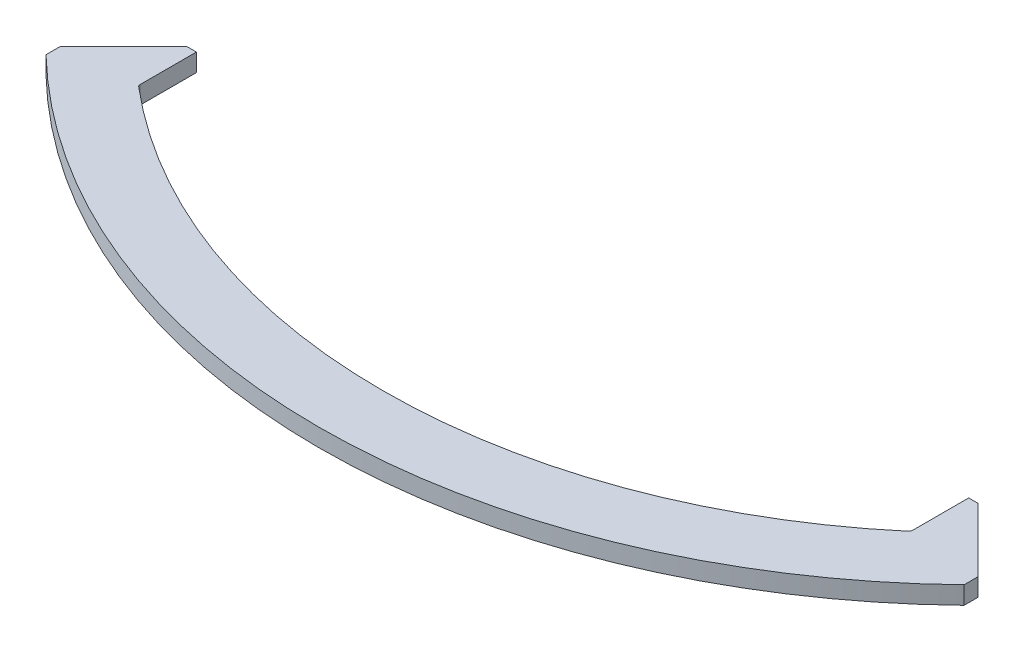
SolidWorks part; units mm, degrees
material "Pine"
ref_plane "Front Plane" through (0, 0, 0) normal (0, 0, 1) x (1, 0, 0)
ref_plane "Top Plane" through (0, 0, 0) normal (0, 1, 0) x (1, 0, 0)
ref_plane "Right Plane" through (0, 0, 0) normal (1, 0, 0) x (0, 0, -1)
sketch "Sketch1" plane through (0, 0, 0) normal (0, 1, 0) x (1, 0, 0)
  line L0 (844.55, 590.55) -> (844.55, -590.55)
  line L1 (-590.55, 862.0125) -> (590.55, 862.0125)
  line L2 (-590.55, 862.0125) -> (-590.55, -862.0125)
  line L3 (-590.55, -862.0125) -> (590.55, -862.0125)
  line L4 (590.55, 862.0125) -> (590.55, -862.0125)
  line L5 (-590.55, 862.0125) -> (590.55, -862.0125) construction
  line L6 (-590.55, -862.0125) -> (590.55, 862.0125) construction
  line L7 (-862.0125, -590.55) -> (862.0125, -590.55)
  line L8 (-862.0125, -590.55) -> (-862.0125, 590.55)
  line L9 (-862.0125, 590.55) -> (862.0125, 590.55)
  line L10 (862.0125, -590.55) -> (862.0125, 590.55)
  line L11 (-862.0125, -590.55) -> (862.0125, 590.55) construction
  line L12 (-862.0125, 590.55) -> (862.0125, -590.55) construction
  circle A0 centre (0, 0) radius 674.6875
  circle A1 centre (0, 0) radius 609.6
  dimension "D1" = 1349.375
  dimension "D2" = 65.0875
  dimension "D3" = 1181.1
  dimension "D4" = 862.0125
  dimension "D5" = 17.4625
sketch "Sketch2" plane through (0, 0, 0) normal (0, 1, 0) x (1, 0, 0)
  line L0 (439.7375, -395.2875) -> (439.7375, -484.1875) construction
  line L13 (484.1875, -484.1875) -> (395.2875, -484.1875)
  line L14 (484.1875, -484.1875) -> (484.1875, -395.2875)
  line L15 (484.1875, -395.2875) -> (395.2875, -395.2875)
  line L16 (395.2875, -484.1875) -> (395.2875, -395.2875)
  line L18 (395.2875, -439.7375) -> (484.1875, -439.7375) construction
  line L20 (-395.2875, -484.1875) -> (-395.2875, -395.2875)
  line L21 (-484.1875, -395.2875) -> (-395.2875, -395.2875)
  line L22 (-484.1875, -484.1875) -> (-484.1875, -395.2875)
  line L23 (-484.1875, -484.1875) -> (-395.2875, -484.1875)
  line L24 (-395.2875, -439.7375) -> (-484.1875, -439.7375) construction
  line L25 (-439.7375, -395.2875) -> (-439.7375, -484.1875) construction
  line L26 (-484.1875, 395.2875) -> (-395.2875, 395.2875)
  line L27 (-395.2875, 484.1875) -> (-395.2875, 395.2875)
  line L28 (-484.1875, 484.1875) -> (-395.2875, 484.1875)
  line L29 (-484.1875, 484.1875) -> (-484.1875, 395.2875)
  line L30 (-439.7375, 395.2875) -> (-439.7375, 484.1875) construction
  line L31 (-395.2875, 439.7375) -> (-484.1875, 439.7375) construction
  line L32 (395.2875, 484.1875) -> (395.2875, 395.2875)
  line L33 (484.1875, 395.2875) -> (395.2875, 395.2875)
  line L34 (484.1875, 484.1875) -> (484.1875, 395.2875)
  line L35 (484.1875, 484.1875) -> (395.2875, 484.1875)
  line L36 (395.2875, 439.7375) -> (484.1875, 439.7375) construction
  line L37 (439.7375, 395.2875) -> (439.7375, 484.1875) construction
  circle A0 centre (0, 0) radius 649.2875
  circle A2 centre (0, 0) radius 649.2875
  circle A3 centre (0, 0) radius 649.2875
  circle A4 centre (0, 0) radius 649.2875
  circle A5 centre (0, 0) radius 674.6875 construction
  point P24 (439.7375, -439.7375)
  point P48 (0, 0)
  dimension "D2" = 25.4
  dimension "D1" = 88.9
  dimension "D4" = 968.375
  dimension "D5" = 968.375
  dimension "D3" = 4
sketch "Sketch3" plane through (0, 0, 0) normal (0, 1, 0) x (1, 0, 0)
  line L8 (469.9, -484.1459) -> (469.9, -469.9)
  line L10 (-469.9, -484.1459) -> (-469.9, -469.9)
  line L11 (395.2875, -484.1875) -> (395.2875, -395.2875) construction
  line L12 (-395.2875, -484.1875) -> (-395.2875, -395.2875) construction
  line L14 (-395.2875, -439.7375) -> (-484.1875, -439.7375) construction
  line L15 (-469.9, -469.9) -> (-404.8125, -404.8125)
  line L19 (395.2875, -464.0689) -> (395.2875, -404.8125)
  line L20 (-395.2875, -464.0689) -> (-395.2875, -404.8125)
  line L21 (-404.8125, -404.8125) -> (-395.2875, -404.8125)
  line L23 (469.9, -469.9) -> (404.8125, -404.8125)
  line L24 (404.8125, -404.8125) -> (395.2875, -404.8125)
  circle A4 centre (0, 0) radius 609.6 construction
  circle A5 centre (0, 0) radius 674.6875 construction
  arc A6 (-395.2875, -464.0689) -> (395.2875, -464.0689) centre (0, 0) ccw
  arc A7 (-469.9, -484.1459) -> (469.9, -484.1459) centre (0, 0) ccw
  point P2 (0, -674.6875)
  point P11 (-439.7375, -439.7375)
  dimension "D1" = 939.8
  dimension "D2" = 269.875
  dimension "D3" = 14.2459
  dimension "D4" = 9.525
extrude "Boss-Extrude1" add sketch "Sketch3" along normal blind 18.2562
fillet "Fillet1" radius 3.3782 2 edges at (395.2875, 9.1281, 464.0689) (-395.2875, 9.1281, 464.0689)
ref_plane "Plane1" through (0, 0, 674.6875) normal (0, 0, 1) x (1, 0, 0)
